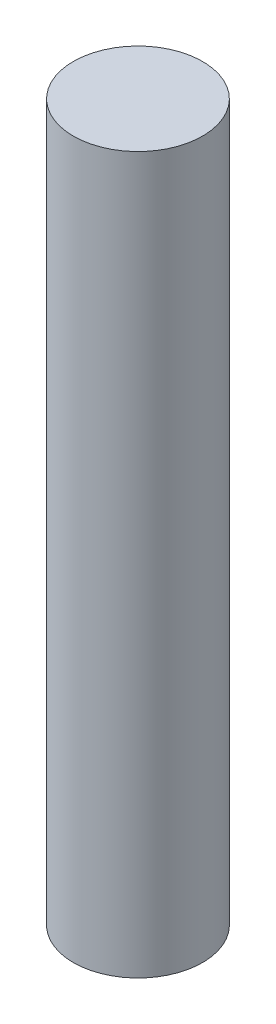
SolidWorks part; units mm, degrees
ref_plane "前视基准面" through (0, 0, 0) normal (0, 0, 1) x (1, 0, 0)
ref_plane "上视基准面" through (0, 0, 0) normal (0, 1, 0) x (1, 0, 0)
ref_plane "右视基准面" through (0, 0, 0) normal (1, 0, 0) x (0, 0, -1)
other "Configuration Table"
sketch "草图1" plane through (0, 0, 0) normal (0, 1, 0) x (1, 0, 0)
  circle A0 centre (0, 0) radius 1.4
  point P0 (-90.6464, 22.0667)
  dimension "D1" = 2.8
extrude "凸台-拉伸1" add sketch "草图1" along normal blind 15.5
